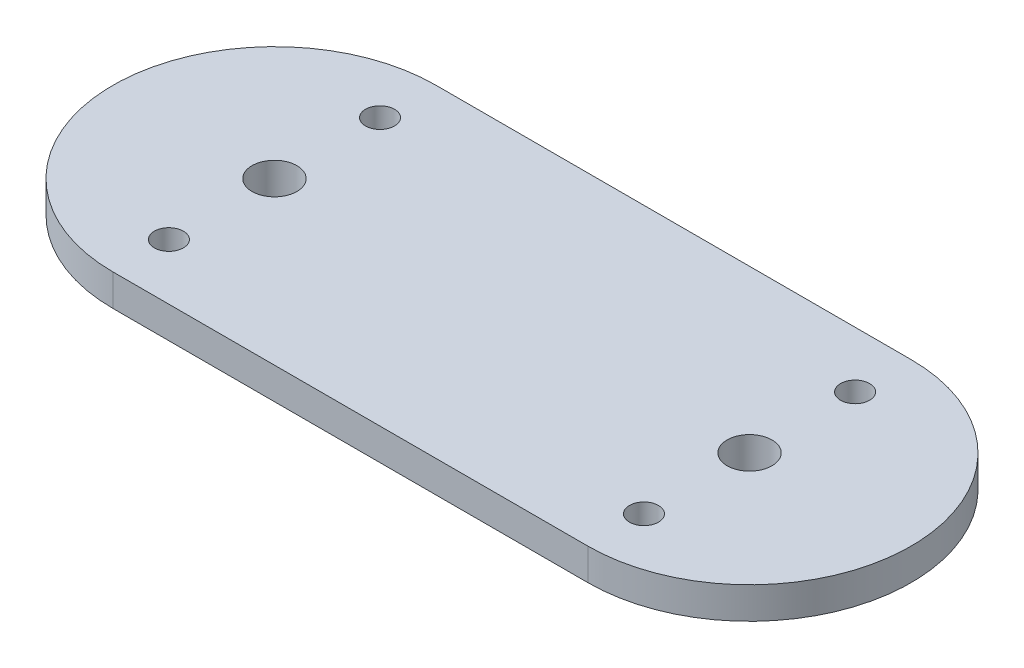
SolidWorks part; units mm, degrees
ref_plane "Front Plane" through (0, 0, 0) normal (0, 0, 1) x (1, 0, 0)
ref_plane "Top Plane" through (0, 0, 0) normal (0, 1, 0) x (1, 0, 0)
ref_plane "Right Plane" through (0, 0, 0) normal (1, 0, 0) x (0, 0, -1)
sketch "Sketch1" plane through (0, 0, 0) normal (0, 1, 0) x (1, 0, 0)
  line L0 (-31.9723, 0) -> (13.0277, 0)
  line L1 (13.0277, -30.6106) -> (-31.9723, -30.6106)
  arc A0 (13.0277, 0) -> (13.0277, -30.6106) centre (13.0277, -15.3053) cw
  arc A1 (-31.9723, -30.6106) -> (-31.9723, 0) centre (-31.9723, -15.3053) cw
  dimension "D1" = 45
  dimension "D2" = 30.6106
extrude "Boss-Extrude1" add sketch "Sketch1" along normal blind 3
sketch "Sketch2" plane through (0, 3, 0) normal (0, 1, 0) x (1, 0, 0)
  line L0 (-9.4723, -54.7734) -> (-9.4723, 0) construction
  line L1 (-31.9723, 0) -> (-31.9723, -30.6106) construction
  line L2 (-54.6054, -15.3053) -> (-9.4723, -15.3053) construction
  line L3 (13.0277, 0) -> (-31.9723, 0) construction
  circle A0 centre (-31.9723, -15.3053) radius 2.125
  circle A1 centre (-31.9723, -5.3053) radius 1.375
  circle A2 centre (-31.9723, -25.3053) radius 1.375
  circle A3 centre (13.0277, -5.3053) radius 1.375
  circle A4 centre (13.0277, -15.3053) radius 2.125
  circle A5 centre (13.0277, -25.3053) radius 1.375
  point P23 (-9.4723, 0)
  dimension "D1" = 4.25
  dimension "D2" = 2.75
  dimension "D3" = 10
extrude "Cut-Extrude1" cut sketch "Sketch2" against normal through all
